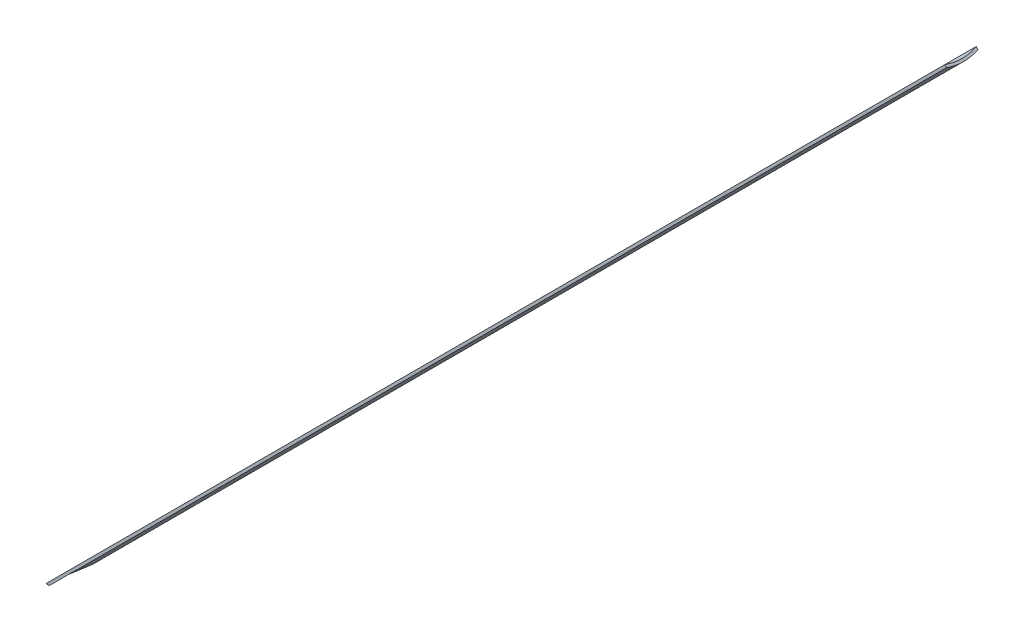
SolidWorks part; units mm, degrees
ref_plane "Front Plane" through (0, 0, 0) normal (0, 0, 1) x (1, 0, 0)
ref_plane "Top Plane" through (0, 0, 0) normal (0, 1, 0) x (1, 0, 0)
ref_plane "Right Plane" through (0, 0, 0) normal (1, 0, 0) x (0, 0, -1)
sketch "Sketch1" plane through (0, 0, 0) normal (0, 0, 1) x (1, 0, 0)
  line L0 (0.3536, 0) -> (-0.3536, 0)
  line L1 (0.3536, 0) -> (4.2426, 3.8891)
  line L4 (4.2426, 3.8891) -> (3.8891, 4.2426)
  line L5 (3.8891, 4.2426) -> (-0.3536, 0)
  point P4 (0, 0)
  dimension "D1" = 45
  dimension "D2" = 0.5
  dimension "D3" = 6
extrude "Boss-Extrude1" add sketch "Sketch1" along normal blind 6.5
sketch "Sketch2" plane through (4.0659, 4.0659, 0) normal (0.7071, 0.7071, 0) x (0, 0, -1)
  line L4 (0, -0.25) -> (0, 0.25)
  line L5 (0, 0.25) -> (-6.5, 0.25)
  line L6 (-6.5, 0.25) -> (-6.5, -0.25)
  line L7 (-6.5, -0.25) -> (0, -0.25)
  line L8 (0, -0.25) -> (0, 0.25)
  line L9 (0, 0.25) -> (-6.5, 0.25)
  line L10 (-6.5, 0.25) -> (-6.5, -0.25)
  line L11 (-6.5, -0.25) -> (0, -0.25)
  dimension "D1" = 0
ref_plane "Plane1" through (6.1872, 6.1872, 0) normal (0.7071, 0.7071, 0) x (0, 0, -1)
sketch "Sketch3" plane through (6.1872, 6.1872, 0) normal (0.7071, 0.7071, 0) x (0, 0, -1)
  line L0 (-6.5, 0.25) -> (-6.5, -0.2731)
  line L1 (0, 0.25) -> (0, -0.2731)
  line L4 (0, -0.25) -> (0, 0.25)
  line L5 (0, 0.25) -> (-6.5, 0.25)
  line L6 (-6.5, 0.25) -> (-6.5, -0.25)
  line L7 (-6.5, -0.25) -> (0, -0.25)
  line L8 (0, -0.25) -> (0, 0.25) construction
  line L9 (0, 0.25) -> (-6.5, 0.25) construction
  line L10 (-6.5, 0.25) -> (-6.5, -0.25) construction
  line L11 (-6.5, -0.25) -> (0, -0.25) construction
  arc A0 (-6.5, 0.25) -> (0, 0.25) centre (-3.25, 10.5625) ccw
  arc A1 (-6.5, -0.2731) -> (0, -0.2731) centre (-3.25, 10.5625) ccw
  arc A2 (-6.6503, -0.2269) -> (0.1503, -0.2269) centre (-3.25, 10.5625) ccw construction
  dimension "D1" = 0
  dimension "D2" = 0.5
loft "Loft1" add profiles "Sketch2", "Sketch3"
sketch "Sketch4" [suppressed] plane through (7.6014, 7.6014, 0) normal (0.7071, 0.7071, 0) x (0, 0, -1)
  line L2 (-6.5, 0.25) -> (-6.5, -0.2731)
  line L3 (0, -0.2731) -> (0, 0.25)
  line L4 (-6.5, 0.25) -> (-6.5, -0.2731)
  line L5 (0, -0.2731) -> (0, 0.25)
  arc A2 (-6.5, 0.25) -> (0, 0.25) centre (-3.25, 10.5625) ccw
  arc A3 (-6.5, -0.2731) -> (0, -0.2731) centre (-3.25, 10.5625) ccw
  arc A4 (-6.5, 0.25) -> (0, 0.25) centre (-3.25, 10.5625) ccw
  arc A5 (-6.5, -0.2731) -> (0, -0.2731) centre (-3.25, 10.5625) ccw
  dimension "D1" = 0
extrude "Boss-Extrude2" [suppressed] add sketch "Sketch4" along normal blind 62
sketch "Sketch5" [suppressed] plane through (7.6014, 7.6014, 0) normal (0.7071, 0.7071, 0) x (0, 0, -1)
  line L2 (-6.5, 0.25) -> (-6.5, -0.2731)
  line L3 (0, -0.2731) -> (0, 0.25)
  line L4 (-6.5, 0.25) -> (-6.5, -0.2731)
  line L5 (0, -0.2731) -> (0, 0.25)
  arc A2 (-6.5, 0.25) -> (0, 0.25) centre (-3.25, 10.5625) ccw
  arc A3 (-6.5, -0.2731) -> (0, -0.2731) centre (-3.25, 10.5625) ccw
  arc A4 (-6.5, 0.25) -> (0, 0.25) centre (-3.25, 10.5625) ccw
  arc A5 (-6.5, -0.2731) -> (0, -0.2731) centre (-3.25, 10.5625) ccw
  dimension "D1" = 0
extrude "Boss-Extrude3" [suppressed] add sketch "Sketch5" along normal blind 28
sketch "Sketch6" plane through (6.1872, 6.1872, 0) normal (0.7071, 0.7071, 0) x (0, 0, -1)
  line L2 (-6.5, 0.25) -> (-6.5, -0.2731)
  line L3 (0, -0.2731) -> (0, 0.25)
  line L4 (-6.5, 0.25) -> (-6.5, -0.2731)
  line L5 (0, -0.2731) -> (0, 0.25)
  arc A2 (-6.5, 0.25) -> (0, 0.25) centre (-3.25, 10.5625) ccw
  arc A3 (-6.5, -0.2731) -> (0, -0.2731) centre (-3.25, 10.5625) ccw
  arc A4 (-6.5, 0.25) -> (0, 0.25) centre (-3.25, 10.5625) ccw
  arc A5 (-6.5, -0.2731) -> (0, -0.2731) centre (-3.25, 10.5625) ccw
  dimension "D1" = 0
extrude "Boss-Extrude4" add sketch "Sketch6" along normal blind 254
sketch "Sketch7" [suppressed] plane through (0, 0, 0) normal (0, 0, 1) x (1, 0, 0)
  line L4 (-6.9619, 12.75) -> (0.3652, 12.75)
  line L5 (0.3652, 13.25) -> (-6.9619, 13.25)
  line L6 (-6.9619, 13.25) -> (-6.9619, 12.75)
  line L7 (3.8891, 4.2426) -> (4.2426, 3.8891)
  circle A0 centre (-6.9619, 7.75) radius 5 construction
  circle A1 centre (-6.9619, 7.75) radius 5 construction
  arc A4 (3.8891, 4.2426) -> (0.3652, 12.75) centre (0.3652, 7.7665) ccw
  arc A5 (4.2426, 3.8891) -> (0.3652, 13.25) centre (0.3652, 7.7665) ccw
  arc A6 (4.2426, 3.8891) -> (0.3652, 13.25) centre (0.3652, 7.7665) ccw construction
  dimension "D2" = 0.5
  dimension "D1" = 0.5
sketch "Sketch8" [suppressed] plane through (0, 0, 0) normal (0, 0, 1) x (1, 0, 0)
  line L4 (-6.4619, 13.25) -> (0.1581, 13.25)
  line L5 (-6.4619, 13.25) -> (-6.4619, 13.75)
  line L6 (-6.4619, 13.75) -> (0.1581, 13.75)
  line L7 (3.8891, 4.2426) -> (4.2426, 3.8891)
  circle A0 centre (-6.4619, 8.25) radius 5 construction
  circle A1 centre (-6.4619, 8.25) radius 5 construction
  arc A4 (3.8891, 4.2426) -> (0.1581, 13.25) centre (0.1581, 7.9736) ccw
  arc A5 (4.2426, 3.8891) -> (0.1581, 13.75) centre (0.1581, 7.9736) ccw
  arc A6 (4.2426, 3.8891) -> (0.1581, 13.75) centre (0.1581, 7.9736) ccw construction
  arc A7 (3.8891, 4.2426) -> (0.1581, 13.25) centre (0.1581, 7.9736) ccw construction
  dimension "D2" = 0.5
  dimension "D1" = 0.5
sketch "Sketch9" [suppressed] plane through (0, 0, 0) normal (0, 0, 1) x (1, 0, 0)
  line L0 (-6.9619, 12.75) -> (0.3652, 12.75)
  line L1 (-6.9619, 12.75) -> (-6.9619, 13.25)
  line L2 (-6.9619, 13.25) -> (0.3652, 13.25)
  line L3 (3.8891, 4.2426) -> (4.2426, 3.8891)
  circle A0 centre (-6.9619, 7.75) radius 5 construction
  circle A1 centre (-6.9619, 7.75) radius 5 construction
  arc A2 (3.8891, 4.2426) -> (0.3652, 12.75) centre (0.3652, 7.7665) ccw
  arc A3 (4.2426, 3.8891) -> (0.3652, 13.25) centre (0.3652, 7.7665) ccw
  arc A4 (4.2426, 3.8891) -> (0.3652, 13.25) centre (0.3652, 7.7665) ccw construction
  arc A5 (3.8891, 4.2426) -> (0.3652, 12.75) centre (0.3652, 7.7665) ccw construction
  dimension "D2" = 0.5
  dimension "D1" = 0.5
extrude "Boss-Extrude7" [suppressed] add sketch "Sketch7" along normal up to surface (6.5 mm away)
extrude "Boss-Extrude8" [suppressed] add sketch "Sketch8" along normal up to surface (6.5 mm away)
extrude "Boss-Extrude9" [suppressed] add sketch "Sketch9" along normal up to surface (6.5 mm away)
sketch "Sketch12" [suppressed] plane through (0, 0, 0) normal (0, 0, 1) x (1, 0, 0)
  circle A0 centre (-6.9619, 7.75) radius 5 construction
  circle A1 centre (-6.9619, 7.75) radius 5
curve "Helix/Spiral1" [suppressed]
sketch "Sketch13" [suppressed] plane through (0, 0, 0) normal (0, 0, 1) x (1, 0, 0)
  line L0 (-6.4707, 13.7499) -> (-6.4619, 13.75)
  line L1 (-6.4619, 13.75) -> (-6.9619, 12.75)
  line L3 (-11.2744, 7.75) -> (-11.2743, 8.2399)
  spline S0 degree 3 poles (-839.9455, -538.3404) (73.381, -56.606) (7.3443, 21.785) (-9.135, 12.599) (-9.7408, 12.0289) (-10.6104, 10.6758) (-10.8735, 9.8943) (-11.0012, 8.3051) (-10.8659, 7.499) (-10.2348, 6.0502) (-9.7397, 5.4089) (-8.511, 4.4376) (-7.7787, 4.1085) (-6.251, 3.8338) (-5.4572, 3.8885) (-3.994, 4.3623) (-3.3258, 4.7809) (-2.2686, 5.8786) (-1.8805, 6.5566) (-1.4697, 8.0096) (-1.4473, 8.7832) (-1.7672, 10.2445) (-2.109, 10.9308) (-3.071, 12.0579) (-3.6902, 12.4977) (-5.057, 13.0328) (-5.8032, 13.1277) (-7.2469, 12.9568) (-7.9429, 12.6912) (-9.1238, 11.8677) (-9.6076, 11.3107) (-17.4835, -4.1644) (62.8135, -61.0203) (430.6273, 906.0957) knots -1.328572 -1.328572 -1.328572 -1.328572 0.0625 0.0625 0.125 0.125 0.1875 0.1875 0.25 0.25 0.3125 0.3125 0.375 0.375 0.4375 0.4375 0.5 0.5 0.5625 0.5625 0.625 0.625 0.6875 0.6875 0.75 0.75 0.8125 0.8125 0.875 0.875 0.9375 0.9375 2.397505 2.397505 2.397505 2.397505 only from (-6.9619, 12.75) to (-11.2744, 7.75) construction
  spline S1 degree 3 poles (-6.9619, 12.75) (-7.7801, 12.7357) (-8.5901, 12.5167) (-10.0072, 11.7267) (-10.613, 11.1566) (-11.4826, 9.8036) (-11.7457, 9.022) (-11.8734, 7.4329) (-11.7381, 6.6267) (-11.107, 5.178) (-10.6119, 4.5367) (-9.3833, 3.5654) (-8.6509, 3.2363) (-7.1233, 2.9616) (-6.3295, 3.0162) (-4.8662, 3.49) (-4.1981, 3.9087) (-3.1409, 5.0064) (-2.7527, 5.6843) (-2.3419, 7.1373) (-2.3195, 7.911) (-2.6394, 9.3723) (-2.9812, 10.0586) (-3.9433, 11.1857) (-4.5625, 11.6255) (-5.9292, 12.1606) (-6.6755, 12.2555) (-8.1191, 12.0845) (-8.8151, 11.8189) (-9.996, 10.9954) (-10.4798, 10.4384) (-11.1264, 9.1679) (-11.2888, 8.4556) (-11.2744, 7.75) knots 0 0 0 0 0.0625 0.0625 0.125 0.125 0.1875 0.1875 0.25 0.25 0.3125 0.3125 0.375 0.375 0.4375 0.4375 0.5 0.5 0.5625 0.5625 0.625 0.625 0.6875 0.6875 0.75 0.75 0.8125 0.8125 0.875 0.875 0.9375 0.9375 1 1 1 1
  spline S2 degree 1 poles (-6.4707, 13.7499) (-11.2743, 8.2399) knots 0 0 1 1 construction
  spline S3 degree 3 poles (-6.4707, 13.7499) (-7.3581, 13.7344) (-9.1599, 13.2519) (-11.1557, 11.3673) (-12.0281, 8.7814) (-11.5796, 6.112) (-9.9392, 3.9865) (-7.5099, 2.8947) (-4.8746, 3.0758) (-2.6545, 4.4667) (-1.3634, 6.7214) (-1.2888, 9.2966) (-2.4276, 11.5834) (-4.4925, 13.0502) (-6.9836, 13.3674) (-9.3095, 12.4794) (-10.9279, 10.6188) (-11.2902, 9.0229) (-11.2743, 8.2399) knots 0 0 0 0 0.0625 0.125 0.1875 0.25 0.3125 0.375 0.4375 0.5 0.5625 0.625 0.6875 0.75 0.8125 0.875 0.9375 1 1 1 1
  dimension "D1" = 0.5
extrude "Boss-Extrude10" [suppressed] add sketch "Sketch13" along normal up to surface (6.5 mm away)
sketch "Sketch14" [suppressed] plane through (0, 0, 0) normal (0, 0, 1) x (1, 0, 0)
  line L0 (0.1581, 13.25) -> (-6.4619, 13.25) construction
  line L1 (-6.4619, 13.75) -> (-15.4619, 13.75)
  line L2 (-6.4619, 13.75) -> (-6.4619, 13.25)
  line L3 (-6.4619, 13.25) -> (-15.4619, 13.25)
  line L4 (-15.4619, 13.75) -> (-15.4619, 13.25)
  dimension "D1" = 9
extrude "Boss-Extrude11" [suppressed] add sketch "Sketch14" along normal up to surface (6.5 mm away)
sketch "Sketch15" [suppressed] plane through (0, 0, 0) normal (0, 0, 1) x (1, 0, 0)
  circle A0 centre (-6.9619, 7.75) radius 5 construction
  circle A1 centre (-6.9619, 7.75) radius 5
curve "Helix/Spiral2" [suppressed]
sketch "Sketch16" [suppressed] plane through (0, 0, 0) normal (0, 0, 1) x (1, 0, 0)
  line L0 (-6.9707, 13.2499) -> (-6.9619, 13.25)
  line L1 (-6.9619, 13.25) -> (-6.9619, 12.75)
  line L4 (-6.9619, 6.875) -> (-6.9122, 6.3775)
  spline S0 degree 3 poles (-872.5208, -487.8798) (63.1551, -64.8618) (7.9001, 19.1468) (-9.3147, 12.1555) (-9.8349, 11.8217) (-10.718, 10.9923) (-11.0808, 10.4969) (-11.6027, 9.4123) (-11.7617, 8.8234) (-11.8575, 7.6315) (-11.7943, 7.0289) (-11.4568, 5.89) (-11.1827, 5.3541) (-10.4627, 4.4193) (-10.017, 4.0207) (-9.0155, 3.4119) (-8.46, 3.2019) (-7.3142, 2.9959) (-6.7244, 3) (-5.5891, 3.2188) (-5.044, 3.4334) (-4.0703, 4.0421) (-3.6419, 4.4359) (-2.9574, 5.348) (-2.7014, 5.866) (-2.3932, 6.9557) (-2.3412, 7.5271) (-2.4454, 8.6469) (-2.6015, 9.1948) (-3.0982, 10.1949) (-3.4387, 10.6467) (-4.2564, 11.3955) (-4.7333, 11.6924) (-5.7584, 12.0937) (-6.3062, 12.1981) (-7.3991, 12.2035) (-7.9439, 12.1044) (-8.958, 11.7187) (-9.4272, 11.4322) (-10.2286, 10.7126) (-10.5606, 10.2796) (-11.0456, 9.3267) (-11.1984, 8.8071) (-11.307, 7.7513) (-11.2627, 7.2156) (-10.986, 6.1992) (-10.7536, 5.7189) (-10.1341, 4.8766) (-9.7473, 4.515) (-8.8729, 3.9565) (-8.3855, 3.7599) (-7.3764, 3.5553) (-6.8549, 3.5474) (-5.8476, 3.7185) (-5.362, 3.8975) (-4.4907, 4.4158) (-4.1051, 4.7549) (-3.4837, 5.546) (-3.248, 5.9977) (-2.9554, 6.9518) (-2.8986, 7.4541) (-2.9686, 8.4417) (-3.0954, 8.9268) (-3.513, 9.8159) (-3.8036, 10.2195) (-4.5076, 10.8931) (-4.9207, 11.1629) (-5.8127, 11.5348) (-6.2913, 11.6368) (-7.2494, 11.6624) (-7.7287, 11.5859) (-8.6244, 11.2674) (-9.0405, 11.0255) (-9.7554, 10.411) (-10.0539, 10.0386) (-10.4959, 9.2149) (-10.6391, 8.7638) (-10.7538, 7.8441) (-10.7253, 7.3757) (-10.503, 6.484) (-10.3094, 6.061) (-9.7855, 5.3156) (-9.4555, 4.9935) (-8.7049, 4.4912) (-8.2847, 4.3111) (-7.4113, 4.1145) (-6.9584, 4.098) (-6.0806, 4.2279) (-5.656, 4.3742) (-4.8908, 4.8076) (-4.5504, 5.0945) (-3.9976, 5.7682) (-3.7853, 6.1549) (-3.5147, 6.975) (-3.4564, 7.4082) (-3.4989, 8.2629) (-3.5996, 8.6841) (-3.9438, 9.4588) (-4.1871, 9.8122) (-4.7816, 10.4055) (-5.1326, 10.6452) (-5.8936, 10.9814) (-6.3035, 11.0778) (-7.1266, 11.1169) (-7.5397, 11.0598) (-8.3142, 10.8024) (-8.6754, 10.6022) (-9.2992, 10.0882) (-9.5615, 9.7745) (-9.9544, 9.0772) (-10.0848, 8.6939) (-10.1991, 7.9097) (-10.1829, 7.5091) (-10.0088, 6.7441) (-9.851, 6.38) (-9.4175, 5.7356) (-9.142, 5.4555) (-8.512, 5.015) (-8.1577, 4.8547) (-7.419, 4.6725) (-7.0348, 4.6508) (-6.2879, 4.7459) (-5.9255, 4.8628) (-5.27, 5.2168) (-4.9771, 5.4538) (-4.4982, 6.0142) (-4.3123, 6.3373) (-4.0701, 7.0251) (-4.0137, 7.3895) (-4.0352, 8.1105) (-4.113, 8.4668) (-4.3897, 9.1244) (-4.5884, 9.4254) (-5.0779, 9.9334) (-5.3684, 10.1403) (-6.0009, 10.4346) (-6.3426, 10.522) (-7.0307, 10.5682) (-7.3769, 10.527) (-8.0279, 10.3246) (-8.3325, 10.1633) (-8.8607, 9.7449) (-9.0841, 9.4878) (-9.4221, 8.914) (-9.5365, 8.5974) (-9.6438, 7.9482) (-9.6366, 7.6157) (-9.5043, 6.9791) (-9.3793, 6.6753) (-9.0309, 6.1357) (-8.8076, 5.9002) (-8.2946, 5.5271) (-8.0051, 5.3896) (-7.3997, 5.2285) (-7.0841, 5.2048) (-6.4692, 5.2717) (-6.1701, 5.3622) (-5.6277, 5.6426) (-5.3844, 5.8323) (-4.9847, 6.2833) (-4.8282, 6.5445) (-4.6206, 7.1019) (-4.5695, 7.3979) (-4.5766, 7.9848) (-4.6347, 8.2754) (-4.8499, 8.813) (-5.0068, 9.0597) (-5.3958, 9.4778) (-5.6278, 9.649) (-6.1343, 9.8954) (-6.4085, 9.9704) (-6.9619, 10.017) (-7.2408, 9.9886) (-7.7661, 9.8349) (-8.0124, 9.7096) (-8.4408, 9.3817) (-8.6227, 9.1791) (-8.8999, 8.7255) (-8.9951, 8.4747) (-9.0888, 7.9595) (-9.0873, 7.6952) (-8.9904, 7.1886) (-8.8951, 6.9464) (-8.6263, 6.5155) (-8.4529, 6.3269) (-8.0532, 6.0267) (-7.827, 5.9151) (-7.3535, 5.7813) (-7.1063, 5.7591) (-6.6242, 5.8043) (-6.3895, 5.8716) (-5.9633, 6.084) (-5.7718, 6.2291) (-5.4562, 6.5751) (-5.3321, 6.776) (-5.1653, 7.2052) (-5.1227, 7.4333) (-5.122, 7.8859) (-5.1638, 8.1101) (-5.3236, 8.5251) (-5.4414, 8.7157) (-5.7347, 9.0393) (-5.9101, 9.1722) (-6.2934, 9.3646) (-6.5011, 9.4241) (-6.9201, 9.4646) (-7.1313, 9.4455) (-7.5291, 9.3342) (-7.7155, 9.2419) (-8.04, 8.9993) (-8.1779, 8.849) (-8.3888, 8.5123) (-8.4616, 8.326) (-8.5353, 7.9437) (-8.536, 7.7477) (-8.4681, 7.3724) (-8.3994, 7.1931) (-8.2047, 6.8743) (-8.0786, 6.7349) (-7.7882, 6.5127) (-7.6239, 6.43) (-7.2804, 6.3299) (-7.1013, 6.3126) (-6.7527, 6.3426) (-6.5833, 6.39) (-6.2762, 6.5405) (-6.1386, 6.6435) (-5.9119, 6.8889) (-5.823, 7.0313) (-5.7032, 7.3347) (-5.6725, 7.4957) (-5.6705, 7.814) (-5.6993, 7.9712) (-5.865, 8.4064) (-6.0833, 8.6443) (-6.6095, 8.9096) (-6.9144, 8.9364) (-7.4514, 8.7857) (-7.6811, 8.6098) (-7.959, 8.163) (-8.0065, 7.8947) (-7.9155, 7.4085) (-7.7781, 7.1928) (-2.7881, 3.4511) (32.6799, 51.9421) (-977.363, 248.3656) knots -0.222446 -0.222446 -0.222446 -0.222446 0.007812 0.007812 0.015625 0.015625 0.023437 0.023437 0.03125 0.03125 0.039062 0.039062 0.046875 0.046875 0.054687 0.054687 0.0625 0.0625 0.070312 0.070312 0.078125 0.078125 0.085937 0.085937 0.09375 0.09375 0.101562 0.101562 0.109375 0.109375 0.117187 0.117187 0.125 0.125 0.132812 0.132812 0.140625 0.140625 0.148437 0.148437 0.15625 0.15625 0.164062 0.164062 0.171875 0.171875 0.179687 0.179687 0.1875 0.1875 0.195312 0.195312 0.203125 0.203125 0.210938 0.210938 0.21875 0.21875 0.226563 0.226563 0.234375 0.234375 0.242188 0.242188 0.25 0.25 0.257813 0.257813 0.265625 0.265625 0.273438 0.273438 0.28125 0.28125 0.289063 0.289063 0.296875 0.296875 0.304688 0.304688 0.3125 0.3125 0.320313 0.320313 0.328125 0.328125 0.335938 0.335938 0.34375 0.34375 0.351563 0.351563 0.359375 0.359375 0.367188 0.367188 0.375 0.375 0.382813 0.382813 0.390625 0.390625 0.398438 0.398438 0.40625 0.40625 0.414063 0.414063 0.421875 0.421875 0.429688 0.429688 0.4375 0.4375 0.445313 0.445313 0.453125 0.453125 0.460938 0.460938 0.46875 0.46875 0.476563 0.476563 0.484375 0.484375 0.492188 0.492188 0.5 0.5 0.507813 0.507813 0.515625 0.515625 0.523438 0.523438 0.53125 0.53125 0.539063 0.539063 0.546875 0.546875 0.554688 0.554688 0.5625 0.5625 0.570313 0.570313 0.578125 0.578125 0.585938 0.585938 0.59375 0.59375 0.601563 0.601563 0.609375 0.609375 0.617188 0.617188 0.625 0.625 0.632813 0.632813 0.640625 0.640625 0.648438 0.648438 0.65625 0.65625 0.664063 0.664063 0.671875 0.671875 0.679688 0.679688 0.6875 0.6875 0.695313 0.695313 0.703125 0.703125 0.710938 0.710938 0.71875 0.71875 0.726563 0.726563 0.734375 0.734375 0.742188 0.742188 0.75 0.75 0.757813 0.757813 0.765625 0.765625 0.773438 0.773438 0.78125 0.78125 0.789063 0.789063 0.796875 0.796875 0.804688 0.804688 0.8125 0.8125 0.820313 0.820313 0.828125 0.828125 0.835938 0.835938 0.84375 0.84375 0.851563 0.851563 0.859375 0.859375 0.867188 0.867188 0.875 0.875 0.882813 0.882813 0.890625 0.890625 0.898438 0.898438 0.90625 0.90625 0.921875 0.921875 0.9375 0.9375 0.953125 0.953125 0.96875 0.96875 0.984375 0.984375 1.389585 1.389585 1.389585 1.389585 only from (-6.9619, 12.75) to (-6.9619, 6.875) construction
  spline S1 degree 3 poles (-6.9619, 12.75) (-7.5755, 12.7393) (-8.1849, 12.6143) (-9.3147, 12.1555) (-9.8349, 11.8217) (-10.718, 10.9923) (-11.0808, 10.4969) (-11.6027, 9.4123) (-11.7617, 8.8234) (-11.8575, 7.6315) (-11.7943, 7.0289) (-11.4568, 5.89) (-11.1827, 5.3541) (-10.4627, 4.4193) (-10.017, 4.0207) (-9.0155, 3.4119) (-8.46, 3.2019) (-7.3142, 2.9959) (-6.7244, 3) (-5.5891, 3.2188) (-5.044, 3.4334) (-4.0703, 4.0421) (-3.6419, 4.4359) (-2.9574, 5.348) (-2.7014, 5.866) (-2.3932, 6.9557) (-2.3412, 7.5271) (-2.4454, 8.6469) (-2.6015, 9.1948) (-3.0982, 10.1949) (-3.4387, 10.6467) (-4.2564, 11.3955) (-4.7333, 11.6924) (-5.7584, 12.0937) (-6.3062, 12.1981) (-7.3991, 12.2035) (-7.9439, 12.1044) (-8.958, 11.7187) (-9.4272, 11.4322) (-10.2286, 10.7126) (-10.5606, 10.2796) (-11.0456, 9.3267) (-11.1984, 8.8071) (-11.307, 7.7513) (-11.2627, 7.2156) (-10.986, 6.1992) (-10.7536, 5.7189) (-10.1341, 4.8766) (-9.7473, 4.515) (-8.8729, 3.9565) (-8.3855, 3.7599) (-7.3764, 3.5553) (-6.8549, 3.5474) (-5.8476, 3.7185) (-5.362, 3.8975) (-4.4907, 4.4158) (-4.1051, 4.7549) (-3.4837, 5.546) (-3.248, 5.9977) (-2.9554, 6.9518) (-2.8986, 7.4541) (-2.9686, 8.4417) (-3.0954, 8.9268) (-3.513, 9.8159) (-3.8036, 10.2195) (-4.5076, 10.8931) (-4.9207, 11.1629) (-5.8127, 11.5348) (-6.2913, 11.6368) (-7.2494, 11.6624) (-7.7287, 11.5859) (-8.6244, 11.2674) (-9.0405, 11.0255) (-9.7554, 10.411) (-10.0539, 10.0386) (-10.4959, 9.2149) (-10.6391, 8.7638) (-10.7538, 7.8441) (-10.7253, 7.3757) (-10.503, 6.484) (-10.3094, 6.061) (-9.7855, 5.3156) (-9.4555, 4.9935) (-8.7049, 4.4912) (-8.2847, 4.3111) (-7.4113, 4.1145) (-6.9584, 4.098) (-6.0806, 4.2279) (-5.656, 4.3742) (-4.8908, 4.8076) (-4.5504, 5.0945) (-3.9976, 5.7682) (-3.7853, 6.1549) (-3.5147, 6.975) (-3.4564, 7.4082) (-3.4989, 8.2629) (-3.5996, 8.6841) (-3.9438, 9.4588) (-4.1871, 9.8122) (-4.7816, 10.4055) (-5.1326, 10.6452) (-5.8936, 10.9814) (-6.3035, 11.0778) (-7.1266, 11.1169) (-7.5397, 11.0598) (-8.3142, 10.8024) (-8.6754, 10.6022) (-9.2992, 10.0882) (-9.5615, 9.7745) (-9.9544, 9.0772) (-10.0848, 8.6939) (-10.1991, 7.9097) (-10.1829, 7.5091) (-10.0088, 6.7441) (-9.851, 6.38) (-9.4175, 5.7356) (-9.142, 5.4555) (-8.512, 5.015) (-8.1577, 4.8547) (-7.419, 4.6725) (-7.0348, 4.6508) (-6.2879, 4.7459) (-5.9255, 4.8628) (-5.27, 5.2168) (-4.9771, 5.4538) (-4.4982, 6.0142) (-4.3123, 6.3373) (-4.0701, 7.0251) (-4.0137, 7.3895) (-4.0352, 8.1105) (-4.113, 8.4668) (-4.3897, 9.1244) (-4.5884, 9.4254) (-5.0779, 9.9334) (-5.3684, 10.1403) (-6.0009, 10.4346) (-6.3426, 10.522) (-7.0307, 10.5682) (-7.3769, 10.527) (-8.0279, 10.3246) (-8.3325, 10.1633) (-8.8607, 9.7449) (-9.0841, 9.4878) (-9.4221, 8.914) (-9.5365, 8.5974) (-9.6438, 7.9482) (-9.6366, 7.6157) (-9.5043, 6.9791) (-9.3793, 6.6753) (-9.0309, 6.1357) (-8.8076, 5.9002) (-8.2946, 5.5271) (-8.0051, 5.3896) (-7.3997, 5.2285) (-7.0841, 5.2048) (-6.4692, 5.2717) (-6.1701, 5.3622) (-5.6277, 5.6426) (-5.3844, 5.8323) (-4.9847, 6.2833) (-4.8282, 6.5445) (-4.6206, 7.1019) (-4.5695, 7.3979) (-4.5766, 7.9848) (-4.6347, 8.2754) (-4.8499, 8.813) (-5.0068, 9.0597) (-5.3958, 9.4778) (-5.6278, 9.649) (-6.1343, 9.8954) (-6.4085, 9.9704) (-6.9619, 10.017) (-7.2408, 9.9886) (-7.7661, 9.8349) (-8.0124, 9.7096) (-8.4408, 9.3817) (-8.6227, 9.1791) (-8.8999, 8.7255) (-8.9951, 8.4747) (-9.0888, 7.9595) (-9.0873, 7.6952) (-8.9904, 7.1886) (-8.8951, 6.9464) (-8.6263, 6.5155) (-8.4529, 6.3269) (-8.0532, 6.0267) (-7.827, 5.9151) (-7.3535, 5.7813) (-7.1063, 5.7591) (-6.6242, 5.8043) (-6.3895, 5.8716) (-5.9633, 6.084) (-5.7718, 6.2291) (-5.4562, 6.5751) (-5.3321, 6.776) (-5.1653, 7.2052) (-5.1227, 7.4333) (-5.122, 7.8859) (-5.1638, 8.1101) (-5.3236, 8.5251) (-5.4414, 8.7157) (-5.7347, 9.0393) (-5.9101, 9.1722) (-6.2934, 9.3646) (-6.5011, 9.4241) (-6.9201, 9.4646) (-7.1313, 9.4455) (-7.5291, 9.3342) (-7.7155, 9.2419) (-8.04, 8.9993) (-8.1779, 8.849) (-8.3888, 8.5123) (-8.4616, 8.326) (-8.5353, 7.9437) (-8.536, 7.7477) (-8.4681, 7.3724) (-8.3994, 7.1931) (-8.2047, 6.8743) (-8.0786, 6.7349) (-7.7882, 6.5127) (-7.6239, 6.43) (-7.2804, 6.3299) (-7.1013, 6.3126) (-6.7527, 6.3426) (-6.5833, 6.39) (-6.2762, 6.5405) (-6.1386, 6.6435) (-5.9119, 6.8889) (-5.823, 7.0313) (-5.7032, 7.3347) (-5.6725, 7.4957) (-5.6705, 7.814) (-5.6993, 7.9712) (-5.865, 8.4064) (-6.0833, 8.6443) (-6.6095, 8.9096) (-6.9144, 8.9364) (-7.4514, 8.7857) (-7.6811, 8.6098) (-7.959, 8.163) (-8.0065, 7.8947) (-7.9155, 7.4085) (-7.7781, 7.1928) (-7.4076, 6.915) (-7.1767, 6.8535) (-6.9619, 6.875) knots 0 0 0 0 0.007812 0.007812 0.015625 0.015625 0.023437 0.023437 0.03125 0.03125 0.039062 0.039062 0.046875 0.046875 0.054687 0.054687 0.0625 0.0625 0.070312 0.070312 0.078125 0.078125 0.085937 0.085937 0.09375 0.09375 0.101562 0.101562 0.109375 0.109375 0.117187 0.117187 0.125 0.125 0.132812 0.132812 0.140625 0.140625 0.148437 0.148437 0.15625 0.15625 0.164062 0.164062 0.171875 0.171875 0.179687 0.179687 0.1875 0.1875 0.195312 0.195312 0.203125 0.203125 0.210938 0.210938 0.21875 0.21875 0.226563 0.226563 0.234375 0.234375 0.242188 0.242188 0.25 0.25 0.257813 0.257813 0.265625 0.265625 0.273438 0.273438 0.28125 0.28125 0.289063 0.289063 0.296875 0.296875 0.304688 0.304688 0.3125 0.3125 0.320313 0.320313 0.328125 0.328125 0.335938 0.335938 0.34375 0.34375 0.351563 0.351563 0.359375 0.359375 0.367188 0.367188 0.375 0.375 0.382813 0.382813 0.390625 0.390625 0.398438 0.398438 0.40625 0.40625 0.414063 0.414063 0.421875 0.421875 0.429688 0.429688 0.4375 0.4375 0.445313 0.445313 0.453125 0.453125 0.460938 0.460938 0.46875 0.46875 0.476563 0.476563 0.484375 0.484375 0.492188 0.492188 0.5 0.5 0.507813 0.507813 0.515625 0.515625 0.523438 0.523438 0.53125 0.53125 0.539063 0.539063 0.546875 0.546875 0.554688 0.554688 0.5625 0.5625 0.570313 0.570313 0.578125 0.578125 0.585938 0.585938 0.59375 0.59375 0.601563 0.601563 0.609375 0.609375 0.617188 0.617188 0.625 0.625 0.632813 0.632813 0.640625 0.640625 0.648438 0.648438 0.65625 0.65625 0.664063 0.664063 0.671875 0.671875 0.679688 0.679688 0.6875 0.6875 0.695313 0.695313 0.703125 0.703125 0.710938 0.710938 0.71875 0.71875 0.726563 0.726563 0.734375 0.734375 0.742188 0.742188 0.75 0.75 0.757813 0.757813 0.765625 0.765625 0.773438 0.773438 0.78125 0.78125 0.789063 0.789063 0.796875 0.796875 0.804688 0.804688 0.8125 0.8125 0.820313 0.820313 0.828125 0.828125 0.835938 0.835938 0.84375 0.84375 0.851563 0.851563 0.859375 0.859375 0.867188 0.867188 0.875 0.875 0.882813 0.882813 0.890625 0.890625 0.898438 0.898438 0.90625 0.90625 0.921875 0.921875 0.9375 0.9375 0.953125 0.953125 0.96875 0.96875 0.984375 0.984375 1 1 1 1
  spline S2 degree 1 poles (-6.9707, 13.2499) (-6.9122, 6.3775) knots 0 0 1 1 construction
  spline S3 degree 3 poles (-6.9707, 13.2499) (-7.6399, 13.2382) (-8.9887, 12.9627) (-11.2802, 11.4953) (-12.8161, 8.3008) (-11.6105, 4.2678) (-8.0545, 2.1174) (-4.0249, 2.9034) (-1.5984, 6.1519) (-1.9784, 10.1378) (-4.9001, 12.8008) (-8.8025, 12.8106) (-11.6621, 10.2302) (-12.0416, 6.4483) (-9.8122, 3.4327) (-6.1847, 2.7068) (-3.0537, 4.5801) (-2.0078, 8.0226) (-3.5242, 11.2292) (-6.7549, 12.5661) (-9.9983, 11.4029) (-11.5951, 8.407) (-10.7773, 5.1644) (-8.0351, 3.3403) (-4.8288, 3.8243) (-2.8114, 6.2977) (-2.9766, 9.4345) (-5.1706, 11.6109) (-8.2073, 11.7461) (-10.5079, 9.8381) (-10.9224, 6.9293) (-9.303, 4.5387) (-6.5466, 3.8687) (-4.0997, 5.2007) (-3.1997, 7.7836) (-4.2494, 10.2543) (-6.6412, 11.357) (-9.1049, 10.5812) (-10.3819, 8.3944) (-9.868, 5.9667) (-7.8967, 4.5444) (-5.5315, 4.8111) (-3.9934, 6.5605) (-4.0302, 8.8389) (-5.5547, 10.4637) (-7.7251, 10.6372) (-9.408, 9.337) (-9.7703, 7.2929) (-8.6905, 5.5795) (-6.7878, 5.0514) (-5.0699, 5.9179) (-4.4002, 7.6675) (-5.0635, 9.3652) (-6.6513, 10.152) (-8.3066, 9.6791) (-9.1855, 8.258) (-8.8878, 6.6653) (-7.6354, 5.7189) (-6.1226, 5.8586) (-5.133, 6.9439) (-5.1336, 8.3623) (-6.0564, 9.372) (-7.3687, 9.4902) (-8.3767, 8.7221) (-8.5924, 7.5243) (-7.9683, 6.5381) (-7.2501, 6.3437) (-6.9122, 6.3775) knots 0 0 0 0 0.007812 0.015625 0.03125 0.046875 0.0625 0.078125 0.09375 0.109375 0.125 0.140625 0.15625 0.171875 0.1875 0.203125 0.21875 0.234375 0.25 0.265625 0.28125 0.296875 0.3125 0.328125 0.34375 0.359375 0.375 0.390625 0.40625 0.421875 0.4375 0.453125 0.46875 0.484375 0.5 0.515625 0.53125 0.546875 0.5625 0.578125 0.59375 0.609375 0.625 0.640625 0.65625 0.671875 0.6875 0.703125 0.71875 0.734375 0.75 0.765625 0.78125 0.796875 0.8125 0.828125 0.84375 0.859375 0.875 0.890625 0.90625 0.921875 0.9375 0.953125 0.96875 0.984375 1 1 1 1
  dimension "D1" = 0.5
extrude "Boss-Extrude12" [suppressed] add sketch "Sketch16" along normal up to surface (6.5 mm away)
